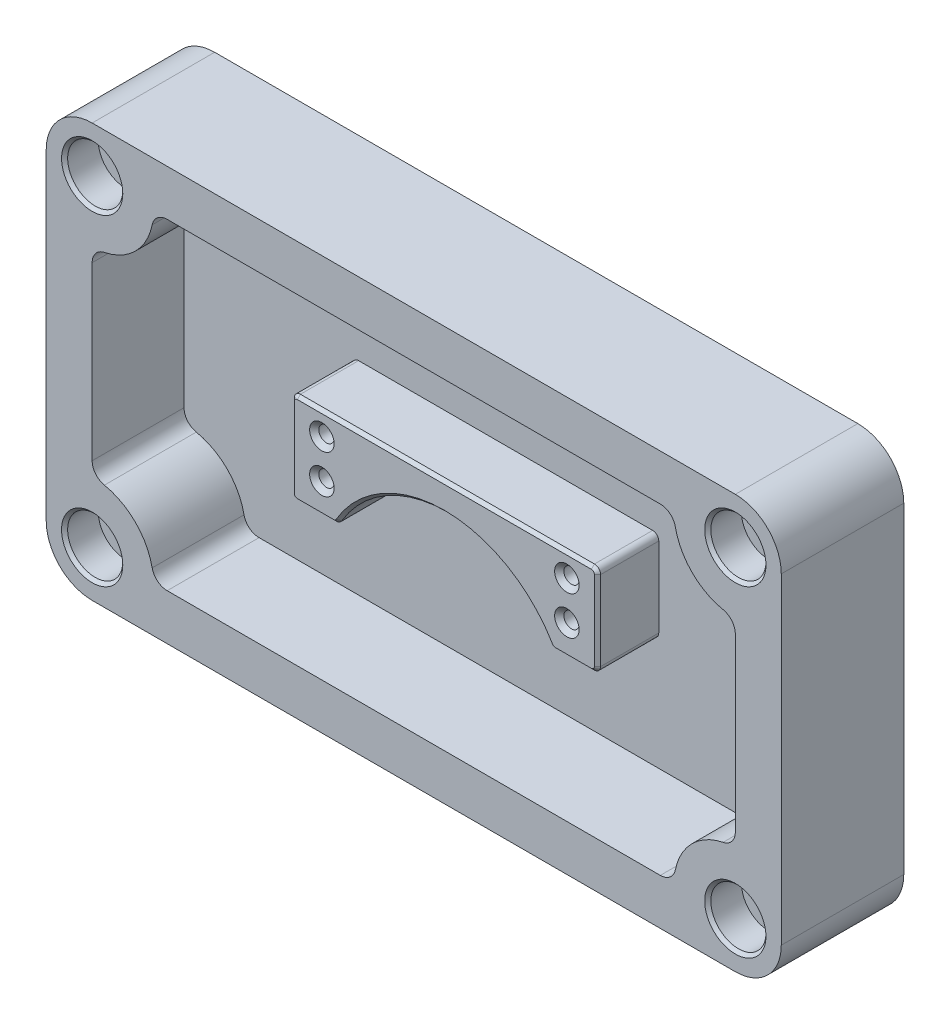
SolidWorks part; units mm, degrees
ref_plane "前视基准面" through (0, 0, 0) normal (0, 0, 1) x (1, 0, 0)
ref_plane "上视基准面" through (0, 0, 0) normal (0, 1, 0) x (1, 0, 0)
ref_plane "右视基准面" through (0, 0, 0) normal (1, 0, 0) x (0, 0, -1)
other "Configuration Table"
sketch "草图1" plane through (0, 0, 0) normal (0, 0, 1) x (1, 0, 0)
  line L0 (0, 15) -> (0, 120)
  line L5 (15, 135) -> (225, 135)
  line L6 (240, 120) -> (240, 15)
  line L11 (225, 0) -> (15, 0)
  line L12 (-12.3825, 67.5) -> (254.7026, 67.5) construction
  line L13 (15, 39.4949) -> (15, 95.5051)
  line L14 (39.4949, 120) -> (200.5051, 120)
  line L15 (225, 95.5051) -> (225, 39.4949)
  line L17 (200.5051, 15) -> (39.4949, 15)
  line L18 (120, 142.6634) -> (120, -9.4836) construction
  arc A0 (240, 120) -> (225, 135) centre (225, 120) ccw
  arc A1 (205.4041, 116) -> (221, 100.4041) centre (225, 120) ccw
  circle A2 centre (225, 120) radius 5.5
  arc A3 (205.4041, 19) -> (221, 34.5959) centre (225, 15) cw
  circle A4 centre (225, 15) radius 5.5
  arc A5 (240, 15) -> (225, 0) centre (225, 15) cw
  arc A6 (34.5959, 19) -> (19, 34.5959) centre (15, 15) ccw
  circle A7 centre (15, 15) radius 5.5
  arc A8 (0, 15) -> (15, 0) centre (15, 15) ccw
  arc A9 (34.5959, 116) -> (19, 100.4041) centre (15, 120) cw
  circle A10 centre (15, 120) radius 5.5
  arc A11 (0, 120) -> (15, 135) centre (15, 120) cw
  arc A12 (19, 100.4041) -> (15, 95.5051) centre (20, 95.5051) ccw
  arc A13 (34.5959, 116) -> (39.4949, 120) centre (39.4949, 115) cw
  arc A14 (205.4041, 116) -> (200.5051, 120) centre (200.5051, 115) ccw
  arc A15 (221, 100.4041) -> (225, 95.5051) centre (220, 95.5051) cw
  arc A16 (221, 34.5959) -> (225, 39.4949) centre (220, 39.4949) ccw
  arc A17 (205.4041, 19) -> (200.5051, 15) centre (200.5051, 20) cw
  arc A18 (34.5959, 19) -> (39.4949, 15) centre (39.4949, 20) ccw
  arc A19 (19, 34.5959) -> (15, 39.4949) centre (20, 39.4949) cw
  point P7 (15, 100)
  point P34 (35, 120)
  point P37 (205, 120)
  point P40 (225, 100)
  point P43 (225, 35)
  point P46 (205, 15)
  point P49 (35, 15)
  point P52 (15, 35)
  dimension "D1" = 120
  dimension "D2" = 5
  dimension "D3" = 11
  dimension "D5" = 15
  dimension "D6" = 15
extrude "凸台-拉伸1" add sketch "草图1" along normal blind 40
sketch "草图2" plane through (0, 0, 0) normal (0, 0, -1) x (-1, 0, 0)
  line L0 (-244.4807, 67.5) -> (9.2441, 67.5) construction
  line L1 (-225, 135) -> (-15, 135)
  line L2 (-240, 120) -> (-240, 15)
  line L3 (-225, 0) -> (-15, 0)
  line L4 (0, 120) -> (0, 15)
  line L5 (-240, 135) -> (0, 0) construction
  line L6 (-240, 0) -> (0, 135) construction
  line L7 (-120, 138.1529) -> (-120, -10.7941) construction
  arc A0 (-240, 15) -> (-225, 0) centre (-225, 15) ccw
  arc A1 (-240, 120) -> (-225, 135) centre (-225, 120) cw
  arc A2 (0, 15) -> (-15, 0) centre (-15, 15) cw
  arc A3 (0, 120) -> (-15, 135) centre (-15, 120) ccw
  point P0 (-120, 67.5)
  dimension "D1" = 135
  dimension "D2" = 240
  dimension "D3" = 67.5
extrude "凸台-拉伸2" add sketch "草图2" against normal blind 10
sketch "草图3" plane through (0, 0, 10) normal (0, 0, 1) x (1, 0, 0)
  line L0 (120, 169.5165) -> (120, -9.3408) construction
  line L2 (-6.7157, 67.5) -> (245.0452, 67.5) construction
  line L3 (15, 0) -> (225, 0) construction
  line L4 (240, 15) -> (240, 120) construction
  line L5 (72, 81.2939) -> (168, 81.2939)
  line L6 (170, 79.2939) -> (170, 53.2939)
  line L7 (168, 51.2939) -> (156.2018, 51.2939)
  line L9 (72, 51.2939) -> (83.7982, 51.2939)
  line L10 (70, 79.2939) -> (70, 53.2939)
  line L11 (120, 0) -> (120, 32)
  circle A1 centre (160, 73.7939) radius 3.6113
  circle A2 centre (80, 73.7939) radius 3.6113
  arc A3 (85.5221, 52.2799) -> (154.4779, 52.2799) centre (120, 32) cw
  circle A4 centre (160, 61.2061) radius 3.6113
  circle A5 centre (80, 61.2061) radius 3.6113
  arc A6 (72, 51.2939) -> (70, 53.2939) centre (72, 53.2939) cw
  arc A7 (170, 53.2939) -> (168, 51.2939) centre (168, 53.2939) cw
  arc A8 (156.2018, 51.2939) -> (154.4779, 52.2799) centre (156.2018, 53.2939) cw
  arc A9 (83.7982, 51.2939) -> (85.5221, 52.2799) centre (83.7982, 53.2939) ccw
  arc A10 (168, 81.2939) -> (170, 79.2939) centre (168, 79.2939) cw
  arc A11 (70, 79.2939) -> (72, 81.2939) centre (72, 79.2939) cw
  point P20 (120, 81.2939)
  point P28 (70, 51.2939)
  point P31 (170, 51.2939)
  point P33 (155.0392, 51.2939)
  point P36 (84.9608, 51.2939)
  point P39 (170, 81.2939)
  point P42 (70, 81.2939)
  dimension "D8" = 40
  dimension "D9" = 2
  dimension "D5" = 2
  dimension "D1" = 67.5
  dimension "D2" = 120
  dimension "D3" = 50
  dimension "D4" = 30
  dimension "D6" = 80
  dimension "D7" = 32
extrude "凸台-拉伸3" add sketch "草图3" along normal blind 20 contours A7 L6 L5 L10 A6 L9 A3 L7 A5 A2 A1 A4
sketch "草图5" plane through (0, 0, 30) normal (0, 0, 1) x (1, 0, 0)
  circle A0 centre (80, 73.7939) radius 3.6113
  circle A1 centre (80, 61.2061) radius 3.6113
  circle A2 centre (160, 73.7939) radius 3.6113
  circle A3 centre (160, 61.2061) radius 3.6113
hole_wizard "M6 螺纹孔3" positions "3D草图3" profile "草图7" tap size "M6" standard "GB"
sketch3d "3D草图3"
  point P0 (80, 73.7939, 30)
  point P3 (80, 61.2061, 30)
  point P6 (160, 73.7939, 30)
  point P9 (160, 61.2061, 30)
cosmetic thread "孔螺蚊线6" parameters "D1"=12, "D2"=6
cosmetic thread "孔螺蚊线7" parameters "D1"=12, "D2"=6
cosmetic thread "孔螺蚊线8" parameters "D1"=12, "D2"=6
cosmetic thread "孔螺蚊线9" parameters "D1"=12, "D2"=6
sketch "草图7" plane through (80, 73.7939, 30) normal (1, 0, 0) x (0, -1, 0)
  line L0 (0, 0) -> (0, 16.5022)
  line L1 (0, 16.5022) -> (2.5, 15)
  line L2 (2.5, 15) -> (2.5, 1.5)
  line L3 (2.5, 1.5) -> (4, 0)
  line L5 (4, 0) -> (0, 0)
  line L6 (-2.5, 1.5) -> (-4, 0) construction
  line L10 (0, 16.5022) -> (-2.5, 15) construction
  line L11 (0, -6.35) -> (0, 107.95) construction
  dimension "螺纹孔钻头直径" = 5
  dimension "螺纹孔钻头深度" = 15
  dimension "近端锥形沉头孔直径" = 8
  dimension "近端锥形沉头孔角度" = 90
  dimension "导头角度" = 118
sketch "草图9" plane through (0, 0, 40) normal (0, 0, 1) x (1, 0, 0)
  circle A0 centre (15, 120) radius 9
  circle A1 centre (15, 15) radius 9
  circle A2 centre (225, 120) radius 9
  circle A3 centre (225, 15) radius 9
extrude "切除-拉伸1" cut sketch "草图9" against normal blind 11
chamfer "倒角2" distance 1 angle 45 4 edges at (234, 15, 40) (234, 120, 40) (24, 15, 40) (24, 120, 40)
chamfer "倒角3" distance 1 angle 45 12 edges at (120, 81.2939, 30) (70.5858, 80.7082, 30) (169.4142, 80.7082, 30) (70, 66.2939, 30) (170, 66.2939, 30) (70.5858, 51.8797, 30) (169.4142, 51.8797, 30) (77.8991, 51.2939, 30) (162.1009, 51.2939, 30) (84.7912, 51.5579, 30) (155.2088, 51.5579, 30) (120, 72, 30)
